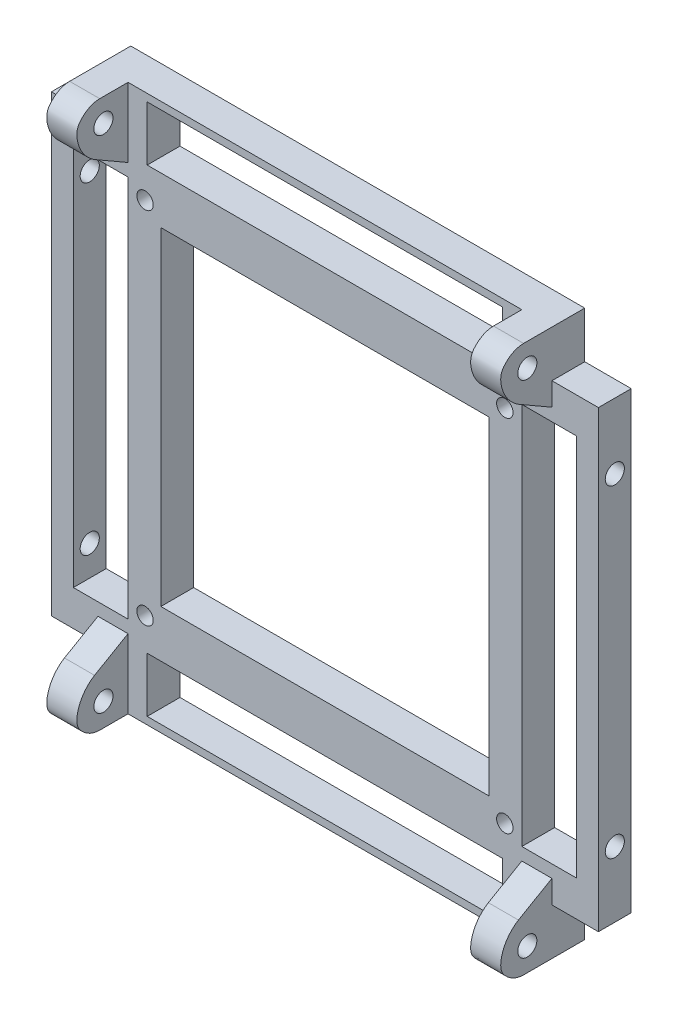
SolidWorks part; units mm, degrees
ref_plane "Front Plane" through (0, 0, 0) normal (0, 0, 1) x (1, 0, 0)
ref_plane "Top Plane" through (0, 0, 0) normal (0, 1, 0) x (1, 0, 0)
ref_plane "Right Plane" through (0, 0, 0) normal (1, 0, 0) x (0, 0, -1)
sketch "Sketch1" plane through (0, 0, 0) normal (0, 0, 1) x (1, 0, 0)
  line L0 (41.5, 50) -> (41.5, 41.5)
  line L1 (-41.5, 50) -> (41.5, 50)
  line L2 (-50, 41.5) -> (-50, -41.5)
  line L3 (-41.5, -50) -> (41.5, -50)
  line L4 (50, 41.5) -> (50, -41.5)
  line L5 (-41.6681, 41.6681) -> (-41.5, 41.5) construction
  line L7 (41.5, 41.5) -> (50, 41.5)
  line L8 (-50, -41.5) -> (-41.5, -41.5)
  line L9 (-41.5, -41.5) -> (-41.5, -50)
  line L10 (0, -55) -> (0, 55) construction
  line L11 (41.5, -41.5) -> (41.5, -50)
  line L12 (50, -41.5) -> (41.5, -41.5)
  line L13 (-50, 41.5) -> (-41.5, 41.5)
  line L15 (-41.5, 50) -> (-41.5, 41.5)
  line L16 (-41.5, 41.5) -> (-50, 41.5)
  point P0 (0, 0)
  dimension "D3" = 8.5
extrude "Boss-Extrude1" add sketch "Sketch1" along normal blind 6 contours L1 L15 L13 L2 L8 L9 L3 L11 L12 L4 L7 L0
sketch "Sketch2" plane through (0, 0, 6) normal (0, 0, 1) x (1, 0, 0)
  point P36 (0, 0)
ref_plane "Plane1" through (41.5, 0, 0) normal (1, 0, 0) x (0, 0, -1)
sketch "Sketch3" plane through (41.5, 0, 0) normal (1, 0, 0) x (0, 0, -1)
  line L0 (-6, 41.5) -> (-6, 37.3)
  line L1 (-6, 41.5) -> (-6, -41.5) construction
  line L2 (-6, 37.3) -> (-12.1228, 40.835)
  line L3 (-6, 50) -> (-11.1789, 50)
  line L4 (-11.1789, 50) -> (-12.1228, 40.835)
  line L5 (-11.6509, 45.4175) -> (-11.6509, 49.9675)
  line L6 (-11.6509, 45.4175) -> (-12.1175, 49.8875)
  line L7 (-11.6509, 45.4175) -> (-14.21, 48.7575)
  line L8 (-11.6509, 45.4175) -> (-15.1209, 47.5875)
  line L9 (-11.6509, 45.4175) -> (-15.1809, 45.0421)
  line L10 (-11.6509, 45.4175) -> (-13.7488, 42.243)
  line L11 (-6, 50) -> (-6, 37.3)
  circle A0 centre (-10.5, 45.75) radius 1.75
  spline S0 degree 3 poles (-11.1789, 50) (-11.4938, 49.9924) (-12.6052, 49.8729) (-14.0499, 49.0428) (-15.4987, 47.3648) (-15.2595, 43.9691) (-13.6433, 41.7946) (-12.1228, 40.835) knots 0 0 0 0 0.074833 0.262848 0.380075 0.581369 1 1 1 1
  point P9 (-10.5, 45.75)
  dimension "D7" = 11.84
  dimension "D1" = 4.2
  dimension "D2" = 60
  dimension "D3" = 7.07
  dimension "D4" = 5.88
  dimension "D5" = 4.25
  dimension "D6" = 4.5
  dimension "D8" = 43.34
  dimension "D9" = 63.86
  dimension "D10" = 101.95
  dimension "D11" = 152.42
  dimension "D12" = 4.55
  dimension "D13" = 4.47
  dimension "D14" = 3.34
  dimension "D15" = 2.17
  dimension "D16" = 3.53
  dimension "D17" = 3.1745
extrude "Boss-Extrude2" add sketch "Sketch3" against normal blind 5.5 contours A0 L4 L2 L0 L11 L3 | L10 S0 L4 A0 | L9 S0 L10 A0 | L8 S0 L9 A0 | L7 S0 L8 A0 | L6 S0 L7 A0 | L5 S0 L6 A0 | L4 S0 L5 A0
mirror "Mirror1" about plane through (0, 0, 0) normal (1, 0, 0) of "Boss-Extrude2"
mirror "Mirror2" about plane through (0, 0, 0) normal (0, 1, 0) of "Mirror1", "Boss-Extrude2"
ref_plane "Plane2" through (-50, 0, 0) normal (-1, 0, 0) x (0, 0, 1)
sketch "Sketch5" plane through (-50, 0, 0) normal (-1, 0, 0) x (0, 0, 1)
  circle A0 centre (3, 29.5) radius 1.75
  point P0 (3, 29.5)
  dimension "D1" = 3
  dimension "D2" = 20.5
extrude "Cut-Extrude3" cut sketch "Sketch5" against normal blind 5.5
ref_plane "Plane3" through (-41.5, 0, 0) normal (-1, 0, 0) x (0, 0, 1)
mirror "Mirror11" about plane through (0, 0, 0) normal (1, 0, 0) of "Cut-Extrude3"
mirror "Mirror12" about plane through (0, 0, 0) normal (0, 1, 0) of "Mirror11", "Cut-Extrude3"
sketch "Sketch18" plane through (0, 0, 6) normal (0, 0, 1) x (1, 0, 0)
  line L0 (-36, 50) -> (36, 50) construction
  line L1 (-30, 30) -> (30, 30)
  line L2 (-30, 30) -> (-30, -30)
  line L3 (-30, -30) -> (30, -30)
  line L4 (30, 30) -> (30, -30)
  line L7 (50, 41.5) -> (50, -41.5) construction
  line L8 (-50, 41.5) -> (-50, -41.5) construction
  line L9 (-50, 41.5) -> (-41.5, 41.5) construction
  line L11 (-46, 35) -> (-36, 35)
  line L12 (-46, 35) -> (-46, -35)
  line L13 (-46, -35) -> (-36, -35)
  line L14 (-36, 35) -> (-36, -35)
  line L15 (46, -35) -> (36, -35)
  line L16 (36, 35) -> (36, -35)
  line L17 (46, 35) -> (36, 35)
  line L18 (46, 35) -> (46, -35)
  line L20 (-32.5, -38.65) -> (32.5, -38.65)
  line L21 (-32.5, 48.65) -> (32.5, 48.65)
  line L22 (-32.5, 48.65) -> (-32.5, 38.65)
  line L23 (-32.5, 38.65) -> (32.5, 38.65)
  line L24 (32.5, 48.65) -> (32.5, 38.65)
  line L25 (32.5, -48.65) -> (32.5, -38.65)
  line L26 (-32.5, -48.65) -> (32.5, -48.65)
  line L27 (-32.5, -48.65) -> (-32.5, -38.65)
  circle A0 centre (-32.89, 32.89) radius 1.5
  circle A1 centre (32.89, 32.89) radius 1.5
  circle A2 centre (32.89, -32.89) radius 1.5
  circle A3 centre (-32.89, -32.89) radius 1.5
  point P0 (0, 0)
  point P10 (-32.89, 32.89)
  point P15 (-45.75, 41.5)
  point P22 (-46, 0)
  point P23 (-50, 0)
  dimension "D5" = 10
  dimension "D1" = 20
  dimension "D2" = 20
  dimension "D3" = 17.11
  dimension "D4" = 8.61
  dimension "D6" = 70
  dimension "D7" = 65
  dimension "D8" = 10
extrude "Cut-Extrude11" cut sketch "Sketch18" against normal through all
